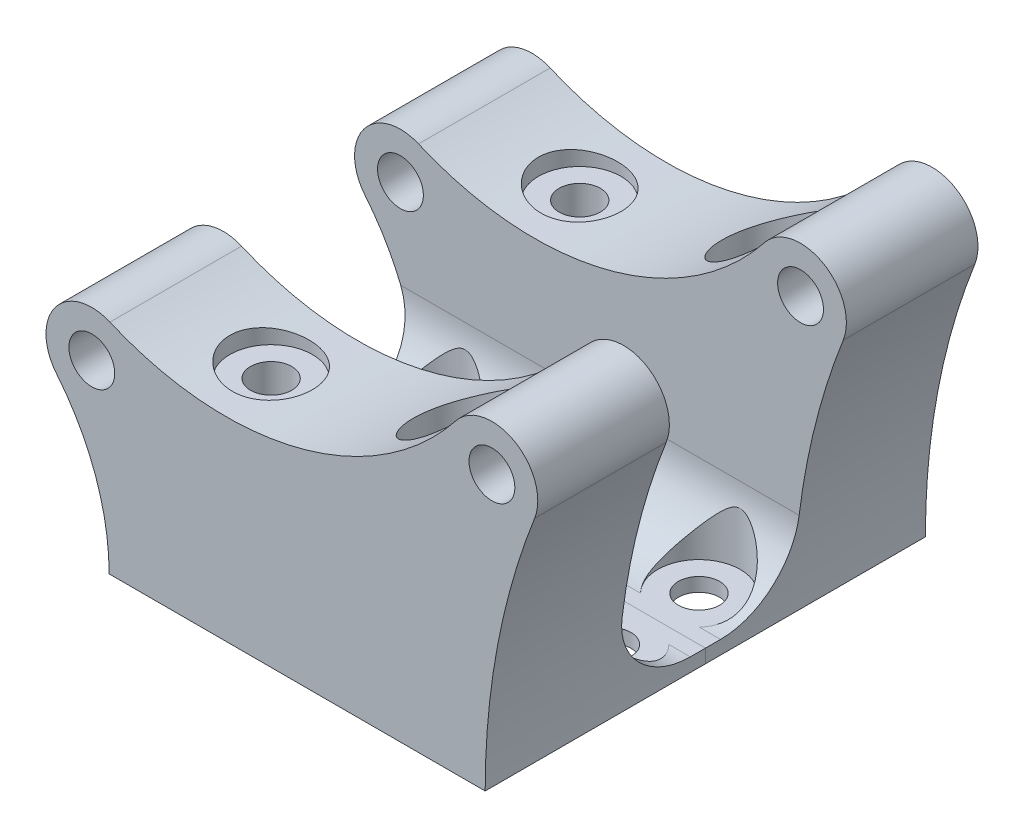
SolidWorks part; units mm, degrees
ref_plane "Płaszczyzna przednia" through (0, 0, 0) normal (0, 0, 1) x (1, 0, 0)
ref_plane "Płaszczyzna górna" through (0, 0, 0) normal (0, 1, 0) x (1, 0, 0)
ref_plane "Płaszczyzna prawa" through (0, 0, 0) normal (1, 0, 0) x (0, 0, -1)
sketch "Szkic1" plane through (0, 0, 0) normal (0, 0, 1) x (1, 0, 0)
  line L0 (-1.47, -60.54) -> (-83.47, -60.54)
  line L1 (-42.47, -60.54) -> (-42.47, -34.6311) construction
  circle A0 centre (-87.247, -22.09) radius 5
  circle A1 centre (0, 0) radius 5
  arc A2 (9.307, -3.6579) -> (-7.8435, 6.2031) centre (0, 0) ccw
  arc A3 (-83.3004, -12.9017) -> (-94.9714, -28.4408) centre (-87.247, -22.09) ccw
  arc A4 (-1.47, -60.54) -> (9.307, -3.6579) centre (154.0338, -60.54) cw
  arc A6 (-83.47, -60.54) -> (-94.9714, -28.4408) centre (-134.0133, -60.54) ccw
  arc A8 (-83.3004, -12.9017) -> (-7.8435, 6.2031) centre (-58.0422, 45.9032) ccw
  dimension "D1" = 10
  dimension "D2" = 10
  dimension "D7" = 20
  dimension "D8" = 20
  dimension "D9" = 155.5038
  dimension "D10" = 64
  dimension "D3" = 90
  dimension "D4" = 82
  dimension "D5" = 60.54
  dimension "D6" = 38.45
extrude "Dodanie-wyciągnięcie1" add sketch "Szkic1" along normal blind 28.7
sketch "Szkic3" plane through (0, 0, 0) normal (1, 0, 0) x (0, 0, -1)
  line L0 (0, -60.54) -> (0, -41.54)
  line L1 (0, -60.54) -> (19.3, -60.54)
  line L2 (-28.7, -60.54) -> (0, -60.54) construction
  line L7 (0, -27.09) -> (0, -17.09) construction
  line L8 (16, -57.54) -> (19.3, -57.54)
  line L9 (19.3, -57.54) -> (19.3, -60.54)
  line L10 (-28.7, -3.6579) -> (-28.7, -60.54) construction
  arc A0 (16, -57.54) -> (0, -41.54) centre (16, -41.54) cw
  dimension "D1" = 48
  dimension "D2" = 3
  dimension "D3" = 19
extrude "Dodanie-wyciągnięcie2" add sketch "Szkic3" against normal up to surface (87.1771 mm away)
sketch "Szkic4" plane through (0, 0, 0) normal (0, 0, 1) x (1, 0, 0)
  line L0 (-1.47, -60.54) -> (0, -60.54)
  line L1 (0, -60.54) -> (0, -41.54)
  line L2 (0, -41.54) -> (-0.3049, -41.54)
  arc A0 (-1.47, -60.54) -> (-0.3049, -41.54) centre (154.0338, -60.54) cw
  arc A1 (-0.3049, -41.54) -> (-1.47, -60.54) centre (154.0338, -60.54) ccw construction
extrude "Wytnij-wyciągnięcie1" cut sketch "Szkic4" against normal up to surface (19.3 mm away) up to face at (-41.7517, -59.0398, -19.3)
hole_wizard "Pogłębienie walcowe pod M8 Wkręt z łbem sześciokątnym z gniazdem1" positions "Szkic7" profile "Szkic9" counterbore size "M8" standard "ISO" end condition through all
sketch "Szkic7" plane through (0, 0, 0) normal (0, 1, 0) x (1, 0, 0)
  line L4 (-17.3275, -14.35) -> (-81.7271, -14.35) construction
  line L7 (-7.8435, 0) -> (-83.3004, 0) construction
  line L8 (-83.3004, -28.7) -> (-7.8435, -28.7) construction
  line L19 (-42.5001, -52.7037) -> (-42.5001, 17.1743) construction
  line L21 (-83.5591, 16) -> (-83.5591, 19.3) construction
  line L22 (-1.441, 19.3) -> (-1.441, 16) construction
  point P0 (-62.5001, -14.35)
  point P2 (-22.5001, -14.35)
  dimension "D1" = 40
sketch "Szkic9" plane through (-62.5001, 0, 14.35) normal (1, 0, 0) x (0, 0, 1)
  line L0 (0, 0) -> (0, 60.54)
  line L1 (0, 60.54) -> (4.5, 60.54)
  line L3 (4.5, 60.54) -> (4.5, 20.3)
  line L4 (4.5, 20.3) -> (9.0055, 20.3)
  line L5 (9.0055, 20.3) -> (9.0055, 0)
  line L7 (9.0055, 0) -> (0, 0)
  line L11 (0, -6.35) -> (0, 107.95) construction
  dimension "Średnica otworu na wylot" = 9
  dimension "Głębokość otworu na wylot" = 60.54
  dimension "Średnica pogłębienia walcowego" = 18.011
  dimension "Głębokość pogłębienia walcowego" = 20.3
hole_wizard "Pogłębienie walcowe pod M8 Wkręt z łbem sześciokątnym z gniazdem3" positions "Szkic10" profile "Szkic11" counterbore size "M8" standard "ISO" end condition through all
sketch "Szkic10" plane through (0, 0, 0) normal (0, 1, 0) x (1, 0, 0)
  line L0 (-25.0973, 9.65) -> (-137.2488, 9.65) construction
  line L3 (-83.5591, 19.3) -> (-1.441, 19.3) construction
  line L4 (-87.1771, 0) -> (-0.3049, 0) construction
  line L5 (-42.5001, -25.0215) -> (-42.5001, 41.234) construction
  line L7 (-1.441, 19.3) -> (-1.441, 16) construction
  line L8 (-83.5591, 16) -> (-83.5591, 19.3) construction
  point P0 (-72.5001, 9.65)
  point P2 (-12.5001, 9.65)
  dimension "D1" = 60
sketch "Szkic11" plane through (-72.5001, 0, -9.65) normal (1, 0, 0) x (0, 0, 1)
  line L0 (0, 0) -> (0, 60.54)
  line L1 (0, 60.54) -> (4.5, 60.54)
  line L3 (4.5, 60.54) -> (4.5, 57.54)
  line L4 (4.5, 57.54) -> (9.0055, 57.54)
  line L5 (9.0055, 57.54) -> (9.0055, 0)
  line L7 (9.0055, 0) -> (0, 0)
  line L11 (0, -6.35) -> (0, 107.95) construction
  dimension "Średnica otworu na wylot" = 9
  dimension "Głębokość otworu na wylot" = 60.54
  dimension "Średnica pogłębienia walcowego" = 18.011
  dimension "Głębokość pogłębienia walcowego" = 57.54
mirror "Lustro2" about plane through (-97.248, -57.54, -19.3) normal (0, 0, -1) of bodies 105
